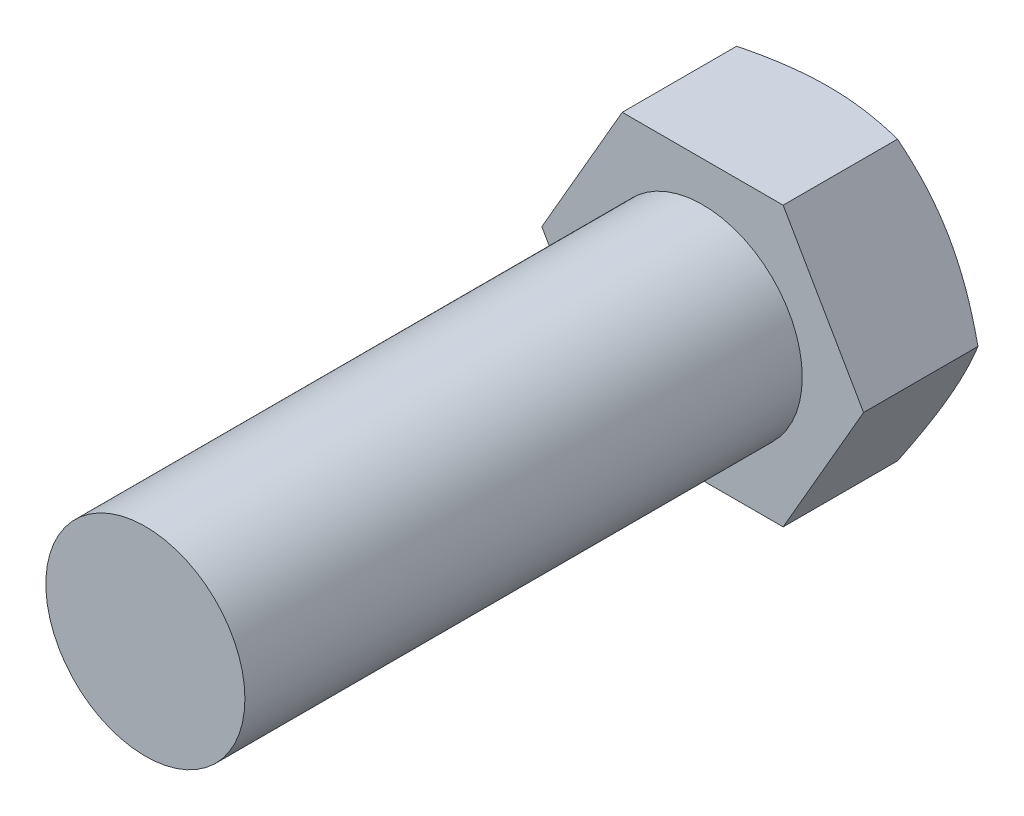
SolidWorks part; units mm, degrees
ref_plane "Alzado" through (0, 0, 0) normal (0, 0, 1) x (1, 0, 0)
ref_plane "Planta" through (0, 0, 0) normal (0, 1, 0) x (1, 0, 0)
ref_plane "Vista lateral" through (0, 0, 0) normal (1, 0, 0) x (0, 0, -1)
sketch "Croquis1" plane through (0, 0, 0) normal (0, 0, 1) x (1, 0, 0)
  line L1 (11.547, 0) -> (5.7735, 10)
  line L2 (5.7735, 10) -> (-5.7735, 10)
  line L3 (-5.7735, 10) -> (-11.547, 0)
  line L4 (-11.547, 0) -> (-5.7735, -10)
  line L5 (-5.7735, -10) -> (5.7735, -10)
  line L6 (5.7735, -10) -> (11.547, 0)
  circle A0 centre (0, 0) radius 10 construction
  dimension "D1" = 20
extrude "Saliente-Extruir1" add sketch "Croquis1" along normal blind 9
sketch "Croquis2" plane through (0, 0, 9) normal (0, 0, 1) x (1, 0, 0)
  circle A0 centre (0, 0) radius 7.1438
  dimension "D1" = 14.2875
extrude "Saliente-Extruir2" add sketch "Croquis2" along normal blind 40
sketch "Croquis3" plane through (0, 0, 0) normal (0, 0, -1) x (-1, 0, 0)
  circle A0 centre (0, 0) radius 10
  circle A1 centre (0, 0) radius 25.7545
extrude "Cortar-Extruir1" cut sketch "Croquis3" against normal blind 3 draft 63
